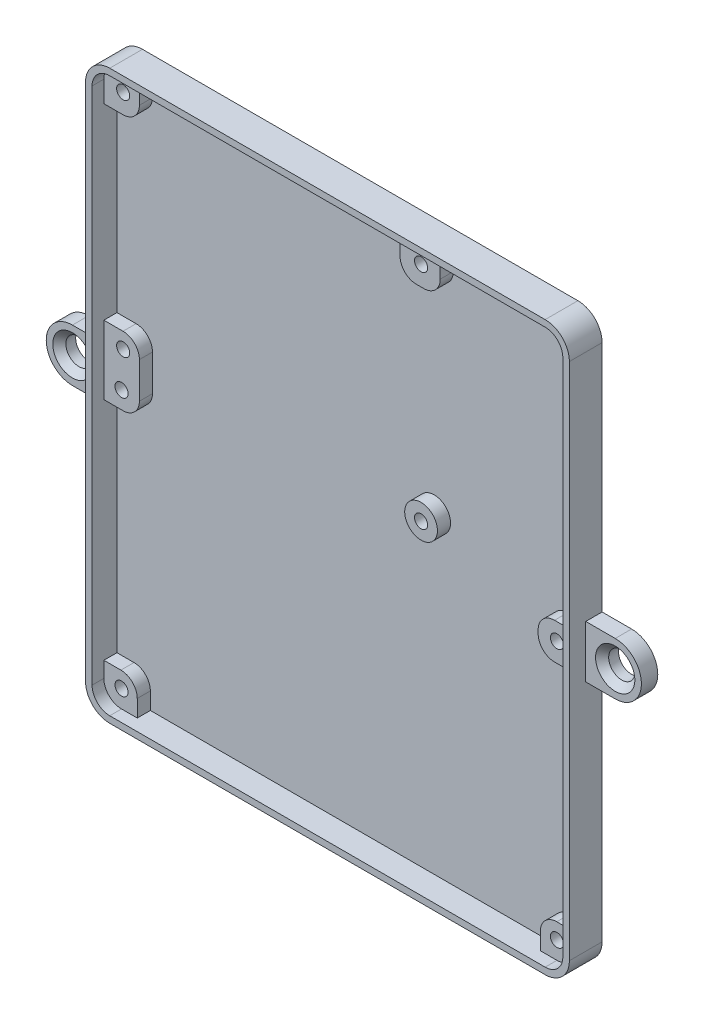
SolidWorks part; units mm, degrees
ref_plane "Спереди" through (0, 0, 0) normal (0, 0, 1) x (1, 0, 0)
ref_plane "Сверху" through (0, 0, 0) normal (0, 1, 0) x (1, 0, 0)
ref_plane "Справа" through (0, 0, 0) normal (1, 0, 0) x (0, 0, -1)
sketch "Эскиз3" plane through (0, 0, 0) normal (0, 0, 1) x (1, 0, 0)
  line L0 (2.5, 84.2) -> (2.5, 84.3)
  line L1 (2.5, 84.3) -> (69, 84.3)
  line L2 (69, 84.3) -> (69, 84.2)
  line L3 (69, 84.2) -> (2.5, 84.2)
  line L4 (71.45, 81.75) -> (71.55, 81.75)
  line L5 (71.55, 81.75) -> (71.55, 2.5)
  line L6 (71.55, 2.5) -> (71.45, 2.5)
  line L7 (71.45, 2.5) -> (71.45, 81.75)
  line L8 (-0.05, 81.75) -> (0.05, 81.75)
  line L9 (0.05, 81.75) -> (0.05, 2.5)
  line L10 (0.05, 2.5) -> (-0.05, 2.5)
  line L11 (-0.05, 2.5) -> (-0.05, 81.75)
  line L12 (2.5, -0.05) -> (2.5, 0.05)
  line L13 (2.5, 0.05) -> (69, 0.05)
  line L14 (69, 0.05) -> (69, -0.05)
  line L15 (69, -0.05) -> (2.5, -0.05)
  circle A0 centre (71.5, 81.75) radius 0.05
  circle A1 centre (71.5, 81.75) radius 0.05
  circle A2 centre (2.5, 84.25) radius 0.05
  circle A3 centre (69, 84.25) radius 0.05
  circle A4 centre (71.5, 81.75) radius 0.05
  circle A5 centre (71.5, 2.5) radius 0.05
  circle A6 centre (0, 81.75) radius 0.05
  circle A7 centre (0, 2.5) radius 0.05
  circle A8 centre (2.5, 0) radius 0.05
  circle A9 centre (69, 0) radius 0.05
  arc A10 (71.5, 81.75) -> (69, 84.25) centre (69, 81.75) ccw
  circle A11 centre (69, 84.25) radius 0.05
  circle A12 centre (71.5, 81.75) radius 0.05
  arc A13 (2.5, 84.25) -> (0, 81.75) centre (2.5, 81.75) ccw
  circle A14 centre (0, 81.75) radius 0.05
  circle A15 centre (2.5, 84.25) radius 0.05
  arc A16 (69, 0) -> (71.5, 2.5) centre (69, 2.5) ccw
  circle A17 centre (71.5, 2.5) radius 0.05
  circle A18 centre (69, 0) radius 0.05
  arc A19 (0, 2.5) -> (2.5, 0) centre (2.5, 2.5) ccw
  circle A20 centre (2.5, 0) radius 0.05
  circle A21 centre (0, 2.5) radius 0.05
  circle A22 centre (69, 2.5) radius 1
  circle A23 centre (69, 42) radius 1
  circle A24 centre (2.5, 42) radius 1
  circle A25 centre (2.5, 2.5) radius 1
  circle A26 centre (48.25, 81.5) radius 1
  circle A27 centre (48.25, 47.5) radius 1
  circle A28 centre (2.75, 47.5) radius 1
  circle A29 centre (2.75, 81.5) radius 1
  circle A30 centre (6, 35.5) radius 0.65
  circle A31 centre (6, 30.5) radius 0.65
  circle A32 centre (6, 24.5) radius 0.65
  circle A33 centre (6, 19.5) radius 0.65
  circle A34 centre (57, 41.5) radius 0.5
  circle A35 centre (59.5, 41.5) radius 0.5
  circle A36 centre (62, 41.5) radius 0.5
  circle A37 centre (54.5, 41.5) radius 0.5
  circle A38 centre (40, 40.75) radius 0.5
  circle A39 centre (37.5, 40.75) radius 0.5
  circle A40 centre (58.25, 29.74) radius 0.5
  circle A41 centre (58.25, 27.2) radius 0.5
  circle A42 centre (58.25, 24.66) radius 0.5
  circle A43 centre (58.25, 22.12) radius 0.5
  circle A44 centre (58.25, 19.58) radius 0.5
  circle A45 centre (58.25, 17.04) radius 0.5
  circle A46 centre (58.25, 14.5) radius 0.5
  circle A47 centre (58.25, 11.96) radius 0.5
  circle A48 centre (35.39, 11.96) radius 0.5
  circle A49 centre (35.39, 14.5) radius 0.5
  circle A50 centre (35.39, 17.04) radius 0.5
  circle A51 centre (35.39, 19.58) radius 0.5
  circle A52 centre (35.39, 22.12) radius 0.5
  circle A53 centre (35.39, 24.66) radius 0.5
  circle A54 centre (35.39, 27.2) radius 0.5
  circle A55 centre (35.34, 29.74) radius 0.5
  circle A56 centre (64, 11.5) radius 0.5
  circle A57 centre (64, 14) radius 0.5
  circle A58 centre (64, 16.5) radius 0.5
  circle A59 centre (6, 8.5) radius 0.65
  circle A60 centre (6, 13.5) radius 0.65
  circle A61 centre (19.75, 7.05) radius 0.65
  circle A62 centre (24.75, 7.05) radius 0.65
  circle A63 centre (14.55, 36.45) radius 0.65
  circle A64 centre (29.95, 36.45) radius 0.65
  circle A65 centre (64, 32.5) radius 0.4
  circle A66 centre (64, 29.96) radius 0.4
  circle A67 centre (64, 27.42) radius 0.4
  circle A68 centre (64, 24.88) radius 0.4
sketch "Эскиз4" plane through (0, 0, 0) normal (0, 0, 1) x (1, 0, 0)
  line L0 (71.7, 81.75) -> (71.7, 2.5)
  line L1 (69, -0.2) -> (2.5, -0.2)
  line L2 (-0.2, 2.5) -> (-0.2, 81.75)
  line L3 (2.5, 84.45) -> (69, 84.45)
  arc A2 (2.5, 84.45) -> (-0.2, 81.75) centre (2.5, 81.75) ccw
  arc A3 (2.5, 84.45) -> (-0.2, 81.75) centre (2.5, 81.75) ccw
  arc A5 (71.7, 81.75) -> (69, 84.45) centre (69, 81.75) ccw
  arc A6 (71.7, 81.75) -> (69, 84.45) centre (69, 81.75) ccw
  arc A8 (-0.2, 2.5) -> (2.5, -0.2) centre (2.5, 2.5) ccw
  arc A9 (-0.2, 2.5) -> (2.5, -0.2) centre (2.5, 2.5) ccw
  arc A11 (69, -0.2) -> (71.7, 2.5) centre (69, 2.5) ccw
  arc A12 (69, -0.2) -> (71.7, 2.5) centre (69, 2.5) ccw
  dimension "D1" = 0.2
  dimension "D2" = 0.2
  dimension "D3" = 0.2
  dimension "D4" = 0.2
extrude "Бобышка-Вытянуть1" add sketch "Эскиз4" along normal blind 1.2
sketch "Эскиз5" plane through (0, 0, 0) normal (0, 0, 1) x (1, 0, 0)
  line L12 (-1.2, 81.75) -> (-1.2, 2.5)
  line L13 (2.5, -1.2) -> (69, -1.2)
  line L14 (72.7, 2.5) -> (72.7, 81.75)
  line L15 (69, 85.45) -> (2.5, 85.45)
  line L16 (-1.2, 81.75) -> (-1.2, 2.5)
  line L17 (2.5, -1.2) -> (69, -1.2)
  line L18 (72.7, 2.5) -> (72.7, 81.75)
  line L19 (69, 85.45) -> (2.5, 85.45)
  line L20 (-0.2, 81.75) -> (-0.2, 2.5)
  line L21 (2.5, -0.2) -> (69, -0.2)
  line L22 (71.7, 2.5) -> (71.7, 81.75)
  line L23 (69, 84.45) -> (2.5, 84.45)
  line L24 (-0.2, 81.75) -> (-0.2, 2.5)
  line L25 (2.5, -0.2) -> (69, -0.2)
  line L26 (71.7, 2.5) -> (71.7, 81.75)
  line L27 (69, 84.45) -> (2.5, 84.45)
  arc A12 (2.5, 85.45) -> (-1.2, 81.75) centre (2.5, 81.75) ccw
  arc A13 (-1.2, 2.5) -> (2.5, -1.2) centre (2.5, 2.5) ccw
  arc A14 (69, -1.2) -> (72.7, 2.5) centre (69, 2.5) ccw
  arc A15 (72.7, 81.75) -> (69, 85.45) centre (69, 81.75) ccw
  arc A16 (2.5, 85.45) -> (-1.2, 81.75) centre (2.5, 81.75) ccw
  arc A17 (-1.2, 2.5) -> (2.5, -1.2) centre (2.5, 2.5) ccw
  arc A18 (69, -1.2) -> (72.7, 2.5) centre (69, 2.5) ccw
  arc A19 (72.7, 81.75) -> (69, 85.45) centre (69, 81.75) ccw
  arc A20 (2.5, 84.45) -> (-0.2, 81.75) centre (2.5, 81.75) ccw
  arc A21 (-0.2, 2.5) -> (2.5, -0.2) centre (2.5, 2.5) ccw
  arc A22 (69, -0.2) -> (71.7, 2.5) centre (69, 2.5) ccw
  arc A23 (71.7, 81.75) -> (69, 84.45) centre (69, 81.75) ccw
  arc A24 (2.5, 84.45) -> (-0.2, 81.75) centre (2.5, 81.75) ccw
  arc A25 (-0.2, 2.5) -> (2.5, -0.2) centre (2.5, 2.5) ccw
  arc A26 (69, -0.2) -> (71.7, 2.5) centre (69, 2.5) ccw
  arc A27 (71.7, 81.75) -> (69, 84.45) centre (69, 81.75) ccw
  dimension "D1" = 1
  dimension "D2" = 0
extrude "Бобышка-Вытянуть2" add sketch "Эскиз5" along normal blind 5
sketch "Эскиз6" plane through (0, 0, 1.2) normal (0, 0, 1) x (1, 0, 0)
  line L0 (2.5, 84.45) -> (5.2261, 84.45)
  line L2 (5.2261, 84.45) -> (5.2261, 81.0078)
  line L3 (2.7261, 78.5078) -> (-0.2, 78.5078)
  line L4 (-0.2, 81.75) -> (-0.2, 2.5) construction
  line L5 (-0.2, 78.5078) -> (-0.2, 81.75)
  line L6 (69, 84.45) -> (2.5, 84.45) construction
  line L7 (-0.2, 2.5) -> (-0.2, 4.8901)
  line L8 (-0.2, 49.8721) -> (2.7261, 49.8721)
  line L9 (-0.2, 49.8721) -> (-0.2, 39.3644)
  line L10 (-0.2, 39.3644) -> (2.7261, 39.3644)
  line L11 (5.2261, 47.3721) -> (5.2261, 41.8644)
  line L12 (-0.2, 4.8901) -> (2.4033, 4.8901)
  line L13 (4.9033, 2.3901) -> (4.9033, -0.2)
  line L14 (2.5, -0.2) -> (69, -0.2) construction
  line L15 (4.9033, -0.2) -> (2.5, -0.2)
  line L16 (69, -0.2) -> (66.4695, -0.2)
  line L17 (2.5, -0.2) -> (69, -0.2) construction
  line L18 (66.4695, -0.2) -> (66.4695, 2.3901)
  line L19 (68.9695, 4.8901) -> (71.7, 4.8901)
  line L20 (71.7, 2.5) -> (71.7, 81.75) construction
  line L21 (71.7, 4.8901) -> (71.7, 2.5)
  line L22 (71.7, 2.5) -> (71.7, 81.75) construction
  line L23 (45.036, 84.45) -> (51.1779, 84.45)
  line L24 (45.036, 84.45) -> (45.036, 80.9868)
  line L25 (47.536, 78.4868) -> (48.6779, 78.4868)
  line L26 (51.1779, 84.45) -> (51.1779, 80.9868)
  line L27 (71.7, 44.5987) -> (68.6318, 44.5987)
  line L28 (71.7, 44.5987) -> (71.7, 39.0793)
  line L29 (71.7, 39.0793) -> (68.6318, 39.0793)
  line L30 (66.1318, 42.0987) -> (66.1318, 41.5793)
  arc A0 (2.5, 84.45) -> (-0.2, 81.75) centre (2.5, 81.75) ccw construction
  arc A1 (2.5, 84.45) -> (-0.2, 81.75) centre (2.5, 81.75) ccw
  arc A2 (5.2261, 81.0078) -> (2.7261, 78.5078) centre (2.7261, 81.0078) cw
  arc A4 (2.7261, 39.3644) -> (5.2261, 41.8644) centre (2.7261, 41.8644) ccw
  arc A5 (5.2261, 47.3721) -> (2.7261, 49.8721) centre (2.7261, 47.3721) ccw
  arc A6 (-0.2, 2.5) -> (2.5, -0.2) centre (2.5, 2.5) ccw construction
  arc A7 (-0.2, 2.5) -> (2.5, -0.2) centre (2.5, 2.5) ccw
  arc A8 (4.9033, 2.3901) -> (2.4033, 4.8901) centre (2.4033, 2.3901) ccw
  arc A9 (69, -0.2) -> (71.7, 2.5) centre (69, 2.5) ccw construction
  arc A10 (69, -0.2) -> (71.7, 2.5) centre (69, 2.5) ccw
  arc A11 (68.9695, 4.8901) -> (66.4695, 2.3901) centre (68.9695, 2.3901) ccw
  arc A12 (48.6779, 78.4868) -> (51.1779, 80.9868) centre (48.6779, 80.9868) ccw
  arc A13 (45.036, 80.9868) -> (47.536, 78.4868) centre (47.536, 80.9868) ccw
  circle A14 centre (48.25, 47.5) radius 2.5
  arc A15 (68.6318, 39.0793) -> (66.1318, 41.5793) centre (68.6318, 41.5793) cw
  arc A16 (68.6318, 44.5987) -> (66.1318, 42.0987) centre (68.6318, 42.0987) ccw
  dimension "D1" = 2.5
  dimension "D2" = 2.5
  dimension "D3" = 2.5
  dimension "D4" = 2.5
  dimension "D5" = 2.5
  dimension "D6" = 5
  dimension "D7" = 2.5
extrude "Бобышка-Вытянуть3" add sketch "Эскиз6" along normal blind 2
sketch "Эскиз7" plane through (0, 0, 3.2) normal (0, 0, 1) x (1, 0, 0)
  circle A0 centre (2.75, 81.5) radius 1
  circle A1 centre (48.25, 81.5) radius 1
  circle A2 centre (48.25, 47.5) radius 1
  circle A3 centre (69, 42) radius 1
  circle A4 centre (2.75, 47.5) radius 1
  circle A5 centre (2.5, 42) radius 1
  circle A6 centre (2.5, 2.5) radius 1
  circle A7 centre (69, 2.5) radius 1
extrude "Вырез-Вытянуть1" cut sketch "Эскиз7" against normal through all
sketch "Эскиз8" plane through (0, 0, 0) normal (0, 0, 1) x (1, 0, 0)
  line L0 (-13.2407, 42.125) -> (85.5267, 42.125) construction
  line L1 (35.75, 99.1277) -> (35.75, -16.9978) construction
  line L2 (-1.2, 81.75) -> (-1.2, 2.5) construction
  line L3 (-5.7, 46.125) -> (-1.2, 46.125)
  line L4 (-1.2, 46.125) -> (-1.2, 38.125)
  line L5 (-1.2, 38.125) -> (-5.7, 38.125)
  line L6 (72.7, 38.125) -> (77.2, 38.125)
  line L7 (72.7, 46.125) -> (72.7, 38.125)
  line L8 (77.2, 46.125) -> (72.7, 46.125)
  circle A0 centre (-5.7, 42.125) radius 2
  arc A1 (-5.7, 46.125) -> (-5.7, 38.125) centre (-5.7, 42.125) ccw
  arc A2 (77.2, 46.125) -> (77.2, 38.125) centre (77.2, 42.125) cw
  circle A3 centre (77.2, 42.125) radius 2
  dimension "D1" = 4.5
extrude "Бобышка-Вытянуть4" add sketch "Эскиз8" along normal blind 2.5
chamfer "Фаска1" distance 1 angle 45 2 edges at (75.2, 42.125, 2.5) (-3.7, 42.125, 2.5)
